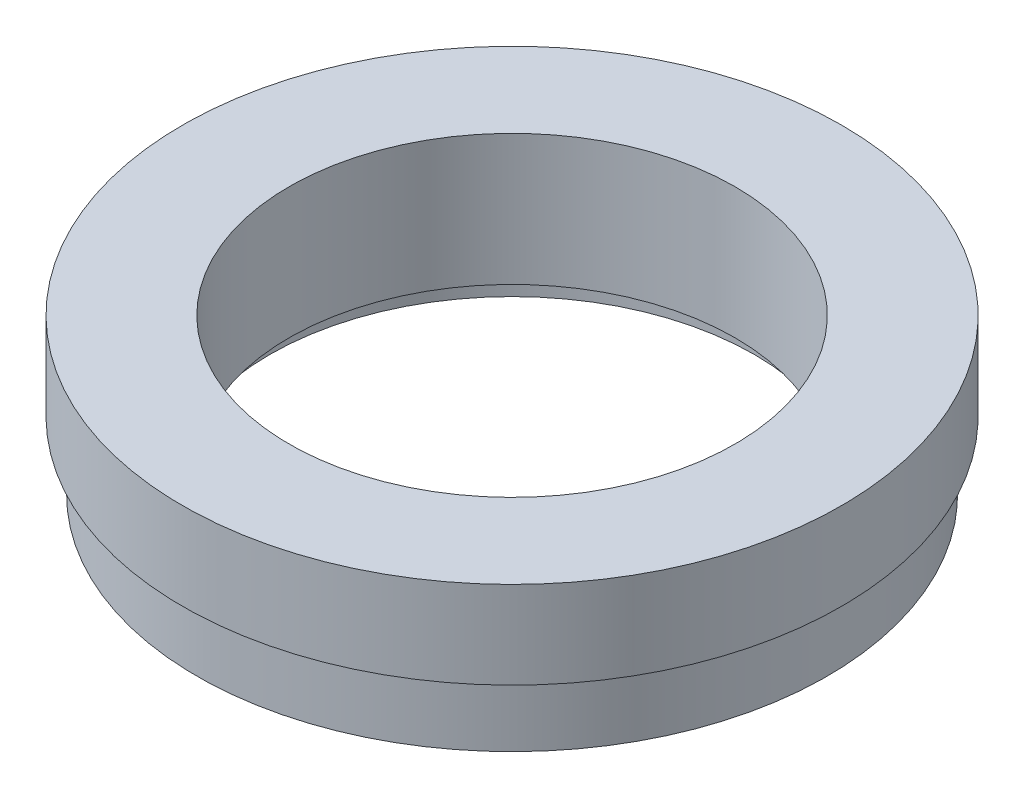
SolidWorks part; units mm, degrees
ref_plane "Front Plane" through (0, 0, 0) normal (0, 0, 1) x (1, 0, 0)
ref_plane "Top Plane" through (0, 0, 0) normal (0, 1, 0) x (1, 0, 0)
ref_plane "Right Plane" through (0, 0, 0) normal (1, 0, 0) x (0, 0, -1)
sketch "Sketch2" plane through (0, 0, 0) normal (0, 0, 1) x (1, 0, 0)
  line L0 (23, 2.5) -> (23, 16)
  line L1 (23, 16) -> (34, 16)
  line L2 (34, 16) -> (34, 7)
  line L3 (34, 7) -> (32.5, 7)
  line L4 (32.5, 7) -> (32.5, 0)
  line L5 (32.5, 0) -> (25, 0)
  line L6 (25, 0) -> (25, 2.5)
  line L7 (25, 2.5) -> (23, 2.5)
  line L8 (0, 0) -> (0, 78.8923) construction
  line L9 (0, 0) -> (25, 0) construction
  dimension "D1" = 46
  dimension "D2" = 50
  dimension "D3" = 16
  dimension "D4" = 2.5
  dimension "D5" = 7
  dimension "D6" = 68
  dimension "D7" = 65
revolve "Revolve1" add sketch "Sketch2" angle 360 about L8
